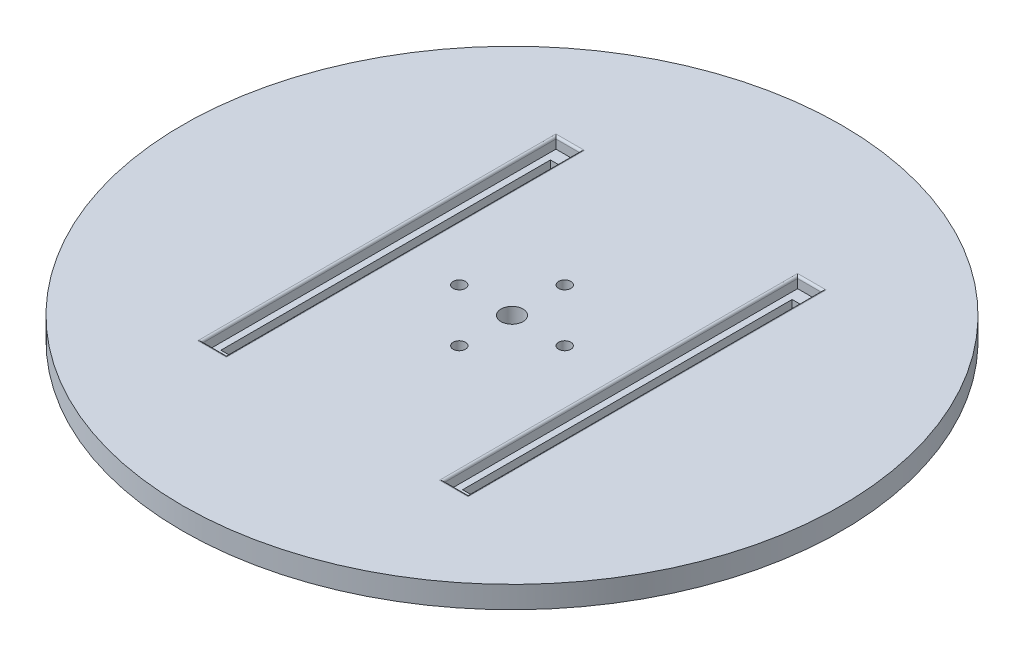
SolidWorks part; units mm, degrees
ref_plane "Front Plane" through (0, 0, 0) normal (0, 0, 1) x (1, 0, 0)
ref_plane "Top Plane" through (0, 0, 0) normal (0, 1, 0) x (1, 0, 0)
ref_plane "Right Plane" through (0, 0, 0) normal (1, 0, 0) x (0, 0, -1)
sketch "Sketch1" plane through (0, 0, 0) normal (0, 1, 0) x (1, 0, 0)
  circle A0 centre (0, 0) radius 75
  dimension "D1" = 150
extrude "Boss-Extrude1" add sketch "Sketch1" along normal blind 5 contours A0
sketch "Sketch2" plane through (0, 5, 0) normal (0, 1, 0) x (1, 0, 0)
  circle A0 centre (0, 0) radius 2.5
  dimension "D1" = 5
extrude "Cut-Extrude1" cut sketch "Sketch2" against normal blind 5
sketch "Sketch3" plane through (0, 5, 0) normal (0, 1, 0) x (1, 0, 0)
  circle A0 centre (0, 12) radius 1.4
  dimension "D1" = 2.8
  dimension "D2" = 12
extrude "Cut-Extrude2" cut sketch "Sketch3" against normal blind 5
pattern_circular "CirPattern1" count 4 over 360 about axis through (0, 0, 0) along (0, 1, 0) of "Cut-Extrude2"
sketch "Sketch4" plane through (0, 5, 0) normal (0, 1, 0) x (1, 0, 0)
  line L1 (-30.25, 40.25) -> (-24.75, 40.25)
  line L2 (-30.25, 40.25) -> (-30.25, -40.25)
  line L3 (-30.25, -40.25) -> (-24.75, -40.25)
  line L4 (-24.75, 40.25) -> (-24.75, -40.25)
  line L5 (-30.25, 40.25) -> (-24.75, -40.25) construction
  line L6 (-30.25, -40.25) -> (-24.75, 40.25) construction
  point P0 (-27.5, 0)
  dimension "D1" = 80.5
  dimension "D2" = 5.5
  dimension "D3" = 0
  dimension "D4" = 27.5
extrude "Cut-Extrude3" cut sketch "Sketch4" against normal blind 2.5
sketch "Sketch5" plane through (0, 2.5, 0) normal (0, 1, 0) x (1, 0, 0)
  line L0 (-30.25, -40.25) -> (-24.75, -40.25) construction
  line L1 (-26.25, 37.5) -> (-28.75, 37.5)
  line L2 (-26.25, 37.5) -> (-26.25, -37.5)
  line L3 (-26.25, -37.5) -> (-28.75, -37.5)
  line L4 (-28.75, 37.5) -> (-28.75, -37.5)
  line L5 (-26.25, 37.5) -> (-28.75, -37.5) construction
  line L6 (-26.25, -37.5) -> (-28.75, 37.5) construction
  point P0 (-27.5, 0)
  point P8 (-27.5, -40.25)
  dimension "D1" = 75
  dimension "D2" = 2.5
  dimension "D3" = 0
  dimension "D4" = 0
extrude "Cut-Extrude4" cut sketch "Sketch5" against normal blind 2.5
fillet "Fillet1" radius 0.5 4 edges at (-27.5, 5, 40.25) (-30.25, 5, 0) (-27.5, 5, -40.25) (-24.75, 5, 0)
pattern_circular "CirPattern2" count 2 over 360 about axis through (0, 0, 0) along (0, 1, 0) of "Cut-Extrude3", "Cut-Extrude4", "Fillet1"
